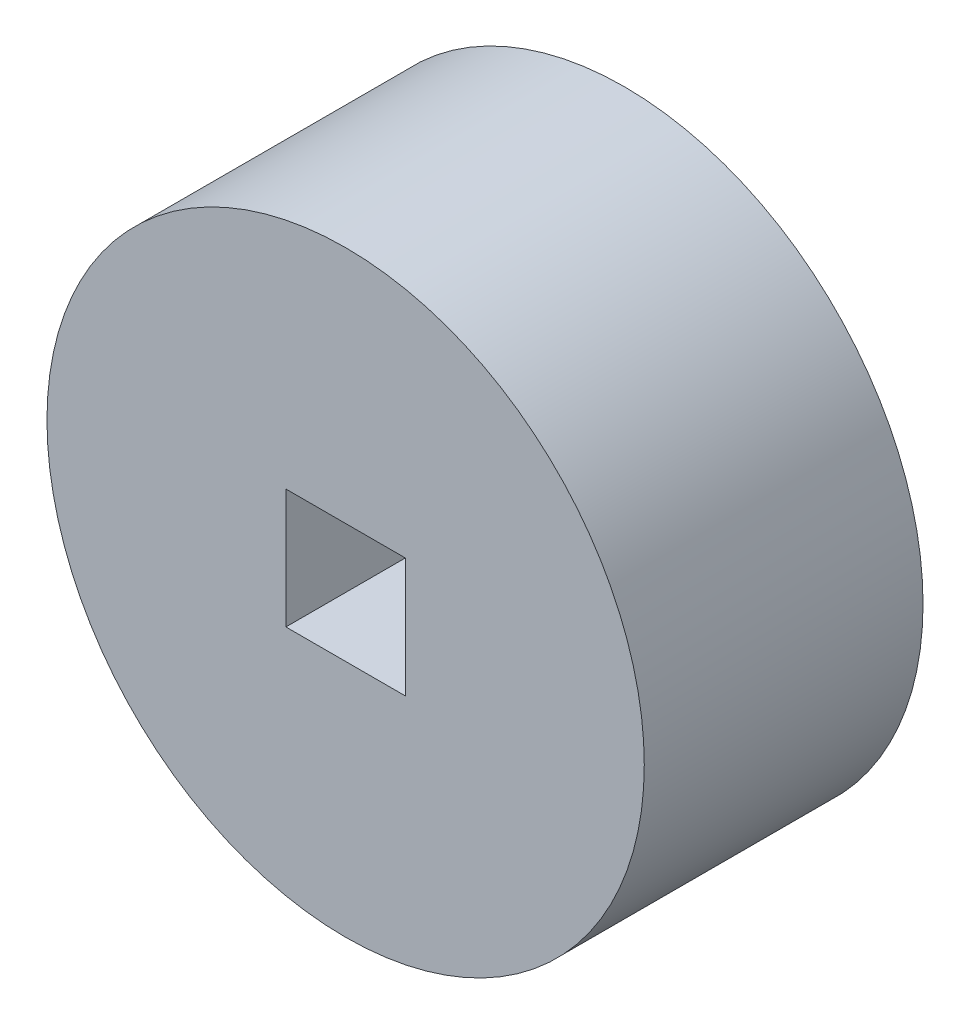
SolidWorks part; units mm, degrees
ref_plane "Front Plane" through (0, 0, 0) normal (0, 0, 1) x (1, 0, 0)
ref_plane "Top Plane" through (0, 0, 0) normal (0, 1, 0) x (1, 0, 0)
ref_plane "Right Plane" through (0, 0, 0) normal (1, 0, 0) x (0, 0, -1)
sketch "Sketch1" plane through (0, 0, 0) normal (0, 0, 1) x (1, 0, 0)
  circle A0 centre (0, 0) radius 7.5
  dimension "D1" = 15
extrude "Boss-Extrude1" add sketch "Sketch1" along normal blind 7
sketch "Sketch2" plane through (0, 0, 0) normal (0, 0, -1) x (-1, 0, 0)
  line L1 (-1.5, -1.5) -> (1.5, -1.5)
  line L2 (-1.5, -1.5) -> (-1.5, 1.5)
  line L3 (-1.5, 1.5) -> (1.5, 1.5)
  line L4 (1.5, -1.5) -> (1.5, 1.5)
  line L5 (-1.5, -1.5) -> (1.5, 1.5) construction
  line L6 (-1.5, 1.5) -> (1.5, -1.5) construction
  point P0 (0, 0)
  dimension "D1" = 3
  dimension "D2" = 3
extrude "Cut-Extrude1" cut sketch "Sketch2" against normal through all
